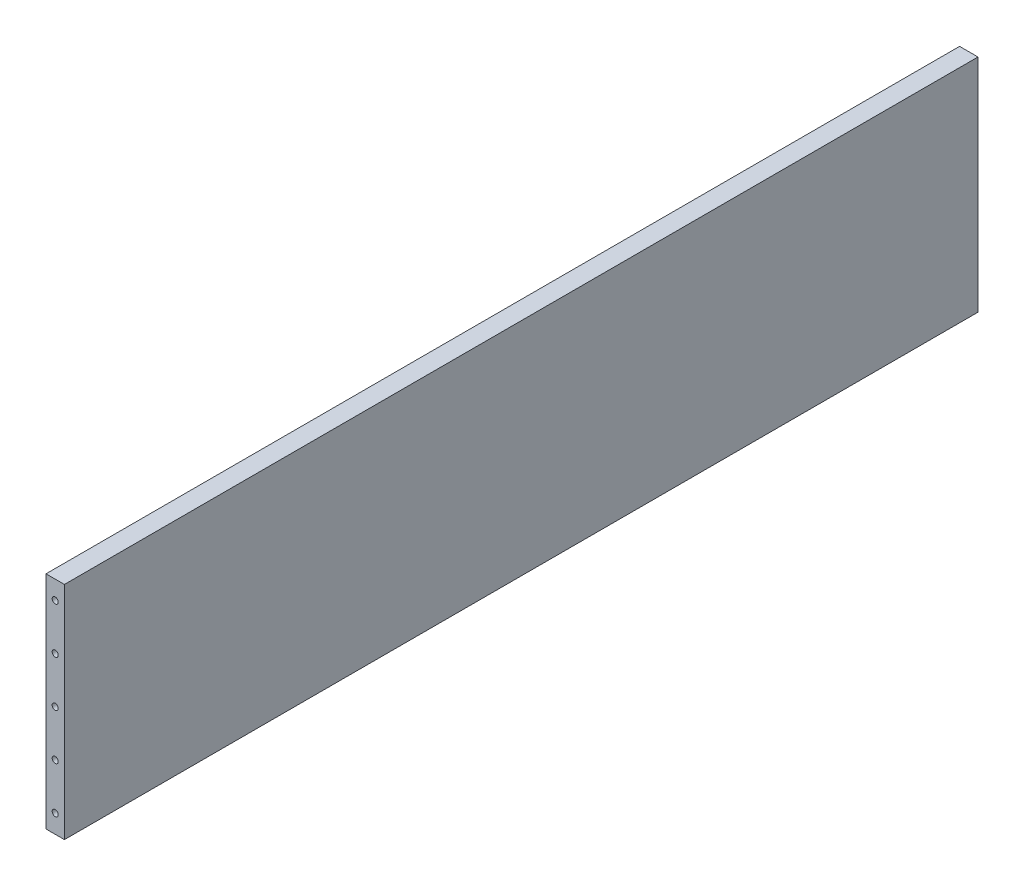
SolidWorks part; units mm, degrees
ref_plane "Front Plane" through (0, 0, 0) normal (0, 0, 1) x (1, 0, 0)
ref_plane "Top Plane" through (0, 0, 0) normal (0, 1, 0) x (1, 0, 0)
ref_plane "Right Plane" through (0, 0, 0) normal (1, 0, 0) x (0, 0, -1)
sketch "Sketch2" plane through (0, 0, 0) normal (0, 0, 1) x (1, 0, 0)
  line L0 (-10, 0) -> (0, 0)
  line L3 (0, 0) -> (0, -120)
  line L4 (0, -120) -> (-10, -120)
  line L5 (-10, -120) -> (-10, 0)
  dimension "D1" = 120
  dimension "D2" = 10
extrude "Boss-Extrude1" add sketch "Sketch2" along normal blind 496
sketch "Sketch3" plane through (0, 0, 496) normal (0, 0, 1) x (1, 0, 0)
  line L0 (-5, 0) -> (-5, -120) construction
  line L1 (0, 0) -> (-10, 0) construction
  line L2 (-10, -120) -> (0, -120) construction
  line L3 (-10, -60) -> (0, -60) construction
  line L4 (-10, 0) -> (-10, -120) construction
  line L5 (0, -120) -> (0, 0) construction
  point P12 (-5, -60)
  point P13 (-5, -110)
  point P14 (-5, -35)
  point P15 (-5, -10)
  point P16 (-5, -85)
  dimension "D1" = 3
hole_wizard "M4 Tapped Hole1" positions "3DSketch1" profile "Sketch4" tap size "M4" standard "ISO"
sketch3d "3DSketch1"
  point P0 (-5, -10, 496)
  point P3 (-5, -35, 496)
  point P6 (-5, -60, 496)
  point P9 (-5, -85, 496)
  point P12 (-5, -110, 496)
sketch "Sketch4" plane through (-5, -10, 496) normal (1, 0, 0) x (0, -1, 0)
  line L0 (0, 0) -> (0, 15.0914)
  line L1 (0, 15.0914) -> (1.65, 14.1)
  line L2 (1.65, 14.1) -> (1.65, 0)
  line L5 (1.65, 0) -> (0, 0)
  line L10 (0, 15.0914) -> (-1.65, 14.1) construction
  line L11 (0, -6.35) -> (0, 107.95) construction
  dimension "Tap Drill Dia." = 3.3
  dimension "Tap Drill Depth" = 14.1
  dimension "Drill Angle" = 118
sketch "Sketch5" plane through (0, 0, 0) normal (0, 0, -1) x (-1, 0, 0)
  line L0 (5, 0) -> (5, -120) construction
  line L1 (0, 0) -> (10, 0) construction
  line L2 (10, -120) -> (0, -120) construction
  line L3 (10, -60) -> (0, -60) construction
  point P10 (5, -60)
  point P11 (5, -85)
  point P12 (5, -35)
  point P13 (5, -10)
  point P14 (5, -110)
  dimension "D1" = 3
hole_wizard "M4 Tapped Hole2" positions "3DSketch2" profile "Sketch6" tap size "M4" standard "ISO"
sketch3d "3DSketch2"
  point P0 (-5, -10, 0)
  point P3 (-5, -35, 0)
  point P6 (-5, -60, 0)
  point P9 (-5, -85, 0)
  point P12 (-5, -110, 0)
sketch "Sketch6" plane through (-5, -10, 0) normal (1, 0, 0) x (0, 1, 0)
  line L0 (0, 0) -> (0, 15.0914)
  line L1 (0, 15.0914) -> (1.65, 14.1)
  line L2 (1.65, 14.1) -> (1.65, 0)
  line L5 (1.65, 0) -> (0, 0)
  line L10 (0, 15.0914) -> (-1.65, 14.1) construction
  line L11 (0, -6.35) -> (0, 107.95) construction
  dimension "Tap Drill Dia." = 3.3
  dimension "Tap Drill Depth" = 14.1
  dimension "Drill Angle" = 118
